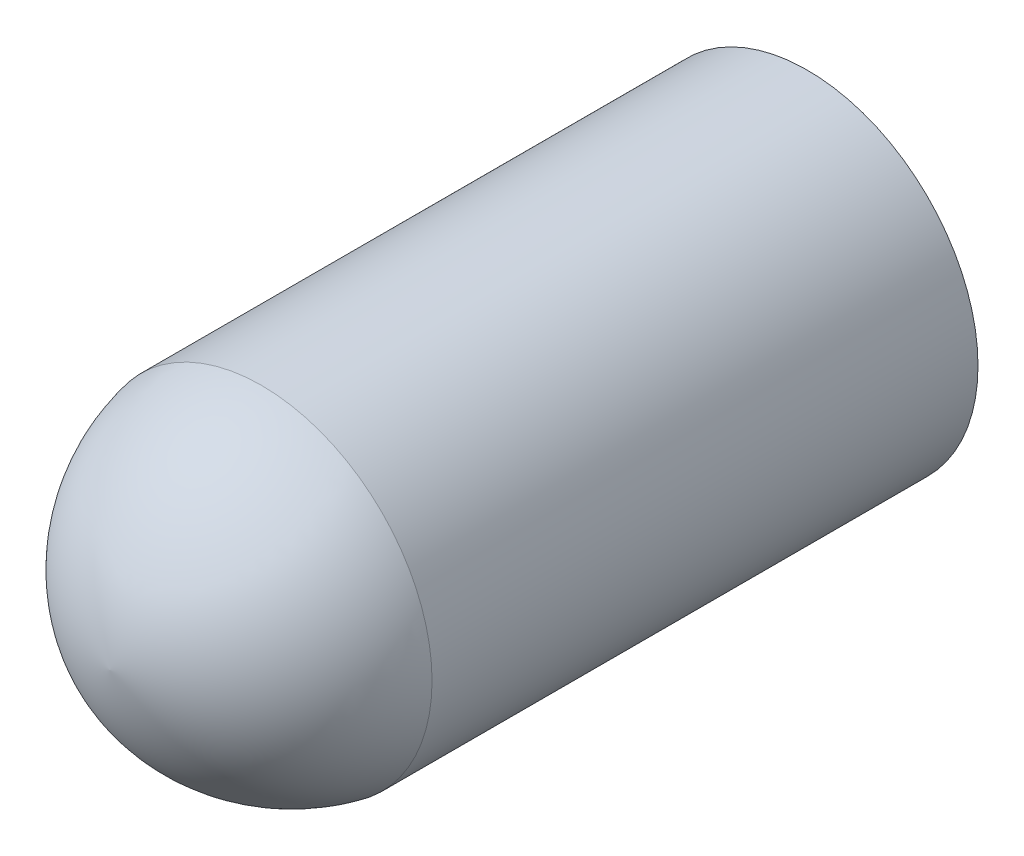
SolidWorks part; units mm, degrees
ref_plane "Front Plane" through (0, 0, 0) normal (0, 0, 1) x (1, 0, 0)
ref_plane "Top Plane" through (0, 0, 0) normal (0, 1, 0) x (1, 0, 0)
ref_plane "Right Plane" through (0, 0, 0) normal (1, 0, 0) x (0, 0, -1)
sketch "Sketch1" plane through (0, 0, 0) normal (0, 0, 1) x (1, 0, 0)
  circle A0 centre (0, 0) radius 22.5
  dimension "D1" = 45
extrude "Boss-Extrude1" add sketch "Sketch1" along normal mid plane 72
sketch "Sketch2" plane through (0, 0, 0) normal (1, 0, 0) x (0, 0, -1)
  line L0 (-36, 0) -> (-56, 0) construction
  line L1 (-36, 22.5) -> (-36, -22.5) construction
  line L2 (-36, 22.5) -> (-36, 0)
  line L3 (-36, 0) -> (-56, 0)
  arc A0 (-36, 22.5) -> (-56, 0) centre (-31.081, -2.0113) ccw
  dimension "D2" = 25
  dimension "D1" = 20
revolve "Revolve1" add sketch "Sketch2" angle 360 about L3
sketch "Sketch3" plane through (0, 0, -36) normal (0, 0, -1) x (-1, 0, 0)
  circle A0 centre (0, 0) radius 15
  dimension "D1" = 30
extrude "Cut-Extrude1" cut sketch "Sketch3" against normal blind 30
